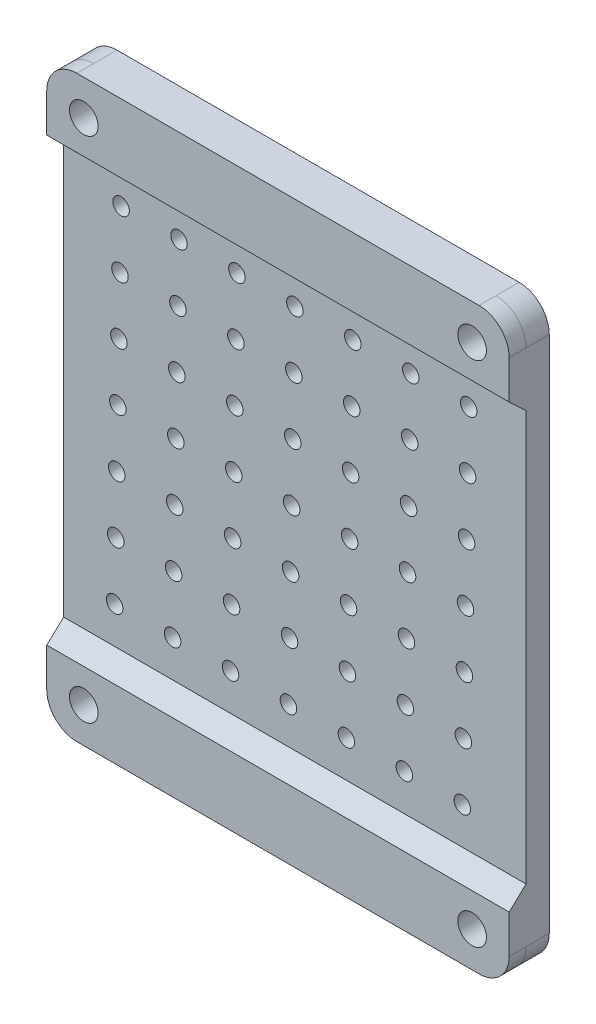
SolidWorks part; units mm, degrees
ref_plane "Front Plane" through (0, 0, 0) normal (0, 0, 1) x (1, 0, 0)
ref_plane "Top Plane" through (0, 0, 0) normal (0, 1, 0) x (1, 0, 0)
ref_plane "Right Plane" through (0, 0, 0) normal (1, 0, 0) x (0, 0, -1)
sketch "Sketch2" plane through (0, 0, 0) normal (0, 0, 1) x (1, 0, 0)
  line L0 (0, 70.0754) -> (0, -70.0754) construction
  line L1 (-68.215, 0) -> (78.5506, 0) construction
  line L2 (-34.7, -49.95) -> (34.7, -49.95)
  line L3 (39.9, -44.75) -> (39.9, 44.75)
  line L4 (-34.7, 49.95) -> (34.7, 49.95)
  line L7 (-39.9, -44.75) -> (-39.9, 44.75)
  circle A0 centre (-33.51, -43.8513) radius 2.47
  arc A1 (-34.7, -49.95) -> (-39.9, -44.75) centre (-34.7, -44.75) cw
  arc A2 (34.7, -49.95) -> (39.9, -44.75) centre (34.7, -44.75) ccw
  circle A3 centre (33.51, -43.8513) radius 2.47
  circle A4 centre (33.51, 43.8513) radius 2.47
  arc A5 (34.7, 49.95) -> (39.9, 44.75) centre (34.7, 44.75) cw
  arc A6 (-34.7, 49.95) -> (-39.9, 44.75) centre (-34.7, 44.75) ccw
  circle A7 centre (-33.51, 43.8513) radius 2.47
  circle A8 centre (28.89, -29.02) radius 1.425
  circle A26 centre (18.8917, -29.02) radius 1.425
  circle A27 centre (8.8933, -29.02) radius 1.425
  circle A28 centre (-1.105, -29.02) radius 1.425
  circle A29 centre (-11.1033, -29.02) radius 1.425
  circle A30 centre (-21.1017, -29.02) radius 1.425
  circle A31 centre (-31.1, -29.02) radius 1.425
  circle A32 centre (19.0758, -19.02) radius 1.425
  circle A33 centre (9.0775, -19.02) radius 1.425
  circle A34 centre (-0.9208, -19.02) radius 1.425
  circle A35 centre (-10.9192, -19.02) radius 1.425
  circle A36 centre (-20.9175, -19.02) radius 1.425
  circle A37 centre (-30.9158, -19.02) radius 1.425
  circle A38 centre (19.26, -9.02) radius 1.425
  circle A39 centre (9.2617, -9.02) radius 1.425
  circle A40 centre (-0.7367, -9.02) radius 1.425
  circle A41 centre (-10.735, -9.02) radius 1.425
  circle A42 centre (-20.7333, -9.02) radius 1.425
  circle A43 centre (-30.7317, -9.02) radius 1.425
  circle A44 centre (19.4442, 0.9801) radius 1.425
  circle A45 centre (9.4458, 0.9801) radius 1.425
  circle A46 centre (-0.5525, 0.9801) radius 1.425
  circle A47 centre (-10.5508, 0.9801) radius 1.425
  circle A48 centre (-20.5492, 0.9801) radius 1.425
  circle A49 centre (-30.5475, 0.9801) radius 1.425
  circle A50 centre (19.6283, 10.9801) radius 1.425
  circle A51 centre (9.63, 10.9801) radius 1.425
  circle A52 centre (-0.3683, 10.9801) radius 1.425
  circle A53 centre (-10.3667, 10.9801) radius 1.425
  circle A54 centre (-20.365, 10.9801) radius 1.425
  circle A55 centre (-30.3633, 10.9801) radius 1.425
  circle A56 centre (19.8125, 20.9801) radius 1.425
  circle A57 centre (9.8142, 20.9801) radius 1.425
  circle A58 centre (-0.1842, 20.9801) radius 1.425
  circle A59 centre (-10.1825, 20.9801) radius 1.425
  circle A60 centre (-20.1808, 20.9801) radius 1.425
  circle A61 centre (-30.1792, 20.9801) radius 1.425
  circle A62 centre (19.9967, 30.9801) radius 1.425
  circle A63 centre (9.9983, 30.9801) radius 1.425
  circle A64 centre (0, 30.9801) radius 1.425
  circle A65 centre (-9.9983, 30.9801) radius 1.425
  circle A66 centre (-19.9967, 30.9801) radius 1.425
  circle A67 centre (-29.995, 30.9801) radius 1.425
  circle A68 centre (29.0742, -19.02) radius 1.425
  circle A69 centre (29.2583, -9.02) radius 1.425
  circle A70 centre (29.4425, 0.9801) radius 1.425
  circle A71 centre (29.6267, 10.9801) radius 1.425
  circle A72 centre (29.8108, 20.9801) radius 1.425
  circle A73 centre (29.995, 30.9801) radius 1.425
  point P12 (-39.9, -49.95)
  point P14 (39.9, 49.95)
  point P17 (0, -49.95)
  point P20 (39.9, -49.95)
  point P26 (39.9, 0)
  point P28 (-39.9, 0)
  point P32 (-39.9, 49.95)
  dimension "D4" = 3.6287
  dimension "D5" = 5.2
  dimension "D6" = 4.94
  dimension "D3" = 33.51
  dimension "D7" = 11.01
  dimension "D9" = 2.85
  dimension "D10" = 7
  dimension "D11" = 7
  dimension "D12" = 8.48
  dimension "D13" = 8.48
  dimension "D1" = 99.9
  dimension "D2" = 79.8
  dimension "D8" = 20.93
extrude "Boss-Extrude1" add sketch "Sketch2" along normal blind 4
sketch "Sketch3" plane through (0, 0, 0) normal (1, 0, 0) x (0, 0, -1)
  line L0 (-4, 49.95) -> (-6.92, 49.95)
  line L1 (-6.92, 49.95) -> (-6.92, 38.11)
  line L2 (-4, -49.95) -> (-4, -35.38)
  line L3 (-4, -44.75) -> (-4, 44.75) construction
  line L4 (-4, -49.95) -> (-6.92, -49.95)
  line L5 (-6.92, 38.11) -> (-4, 35.3762)
  line L6 (-4, 49.95) -> (-4, 35.3762)
  line L7 (-6.92, -49.95) -> (-6.92, -38.11)
  line L8 (-6.92, -38.11) -> (-4, -35.38)
  dimension "D1" = 2.92
  dimension "D2" = 11.84
  dimension "D3" = 4
  dimension "D4" = 14.57
extrude "Boss-Extrude3" add sketch "Sketch3" along normal mid plane 79.8
fillet "Fillet6" radius 5.2 4 edges at (39.9, 49.95, 5.46) (-39.9, 49.95, 5.46) (-39.9, -49.95, 5.46) (39.9, -49.95, 5.46)
sketch "Sketch7" plane through (0, 0, 4) normal (0, 0, -1) x (-1, 0, 0)
  circle A0 centre (-33.51, 43.8513) radius 2.47
  circle A1 centre (33.51, 43.8513) radius 2.47
  circle A2 centre (33.51, -43.8513) radius 2.47
  circle A3 centre (-33.51, -43.8513) radius 2.47
extrude "Cut-Extrude2" cut sketch "Sketch7" against normal mid plane 79.8
